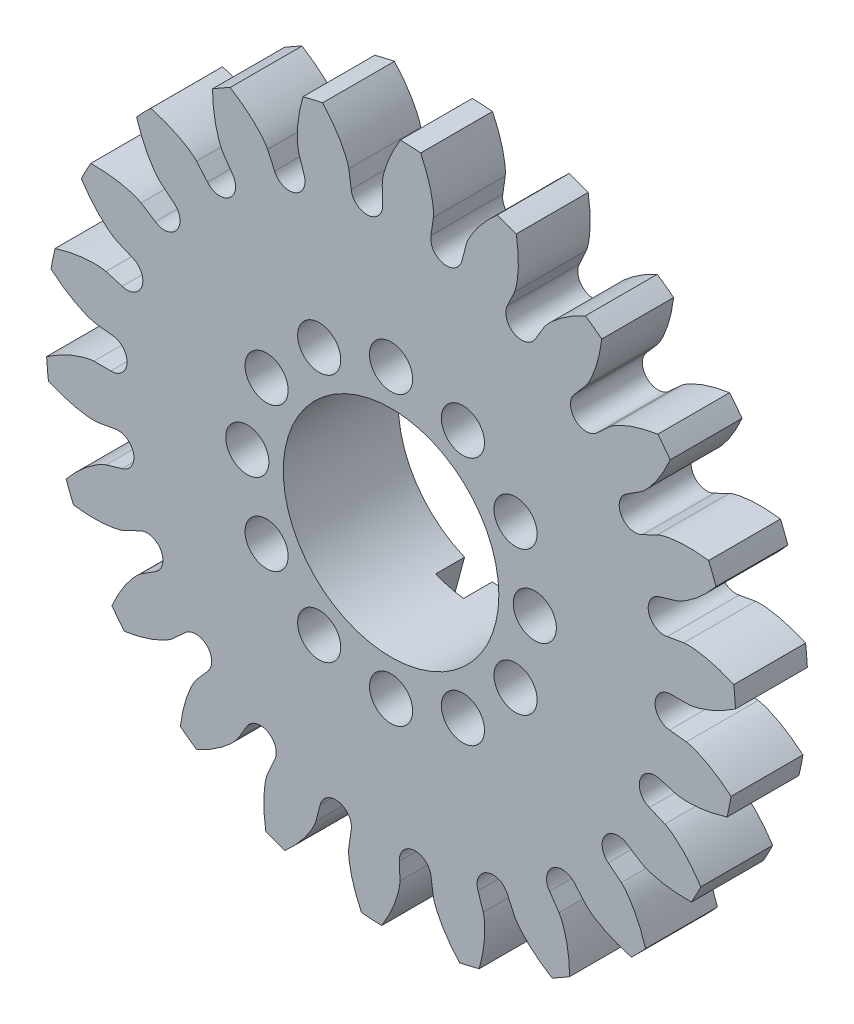
SolidWorks part; units mm, degrees
material "A2017"
ref_plane "正面" through (0, 0, 0) normal (0, 0, 1) x (1, 0, 0)
ref_plane "平面" through (0, 0, 0) normal (0, 1, 0) x (1, 0, 0)
ref_plane "右側面" through (0, 0, 0) normal (1, 0, 0) x (0, 0, -1)
sketch "ｽｹｯﾁ1" plane through (0, 0, 0) normal (1, 0, 0) x (0, 0, -1)
  line L0 (0, 0) -> (5.1985, 0) construction
  line L1 (0, 7.5) -> (5, 7.5)
  line L2 (5, 7.5) -> (5, 17.5)
  line L3 (5, 17.5) -> (0, 17.5)
  line L4 (0, 17.5) -> (0, 7.5)
  dimension "D1" = 35
  dimension "D3" = 5
  dimension "D5" = 15
revolve "回転1" add sketch "ｽｹｯﾁ1" angle 360 about L0
hole_wizard "M3 ねじ穴1" [suppressed] positions "ｽｹｯﾁ2" profile "ｽｹｯﾁ3" tap size "M3" standard "JIS"
sketch "ｽｹｯﾁ2" plane through (0, 0, -0.9) normal (0, 0, 1) x (1, 0, 0)
  point P0 (10, 0)
  point P3 (-5, 8.6603)
  point P6 (-5, -8.6603)
sketch "ｽｹｯﾁ3" plane through (10, 0, -0.9) normal (1, 0, 0) x (0, -1, 0)
  line L0 (0, 0) -> (0, 2)
  line L1 (0, 2) -> (1.25, 2)
  line L2 (1.25, 2) -> (1.25, 0)
  line L5 (1.25, 0) -> (0, 0)
  line L11 (0, -6.35) -> (0, 107.95) construction
  dimension "次ｻｰﾌｪｽまでのねじ下穴ﾄﾞﾘﾙ直径" = 2.5
  dimension "次ｻｰﾌｪｽまでのねじ下穴ﾄﾞﾘﾙの深さ" = 2
cosmetic thread "穴のねじ山1" [suppressed] parameters "D2"=3
cosmetic thread "穴のねじ山2" [suppressed] parameters "D2"=3
cosmetic thread "穴のねじ山3" [suppressed] parameters "D2"=3
sketch "ｽｹｯﾁ4" [suppressed] plane through (0, 0, -0.9) normal (0, 0, 1) x (1, 0, 0)
  line L0 (10, 0) -> (13.5, 0) construction
  line L1 (10, 3) -> (13.5, 3)
  line L2 (10, -3) -> (13.5, -3)
  line L3 (-5, -8.6603) -> (-6.75, -11.6913) construction
  line L4 (-2.4019, -10.1603) -> (-4.1519, -13.1913)
  line L5 (-7.5981, -7.1603) -> (-9.3481, -10.1913)
  line L6 (-5, 8.6603) -> (-6.75, 11.6913) construction
  line L7 (-7.5981, 7.1603) -> (-9.3481, 10.1913)
  line L8 (-2.4019, 10.1603) -> (-4.1519, 13.1913)
  line L9 (0, 0) -> (10, 0) construction
  circle A0 centre (0, 0) radius 13.5
  arc A1 (10, 3) -> (10, -3) centre (10, 0) ccw
  arc A2 (13.5, -3) -> (13.5, 3) centre (13.5, 0) ccw
  arc A3 (-2.4019, -10.1603) -> (-7.5981, -7.1603) centre (-5, -8.6603) ccw
  arc A4 (-9.3481, -10.1913) -> (-4.1519, -13.1913) centre (-6.75, -11.6913) ccw
  arc A5 (-7.5981, 7.1603) -> (-2.4019, 10.1603) centre (-5, 8.6603) ccw
  arc A6 (-4.1519, 13.1913) -> (-9.3481, 10.1913) centre (-6.75, 11.6913) ccw
  circle A7 centre (0, 0) radius 6
  arc A8 (5.44, 2.5311) -> (7.8667, 2.1092) centre (6.8, 3.1639) ccw
  arc A9 (5.44, -2.5311) -> (7.8667, -2.1092) centre (6.8, -3.1639) cw
  arc A10 (-4.912, -3.4456) -> (-5.76, -5.7581) centre (-6.14, -4.307) cw
  arc A11 (-0.528, -5.9767) -> (-2.1067, -7.8674) centre (-0.66, -7.4709) ccw
  arc A12 (-0.528, 5.9767) -> (-2.1067, 7.8674) centre (-0.66, 7.4709) cw
  arc A13 (-4.912, 3.4456) -> (-5.76, 5.7581) centre (-6.14, 4.307) ccw
  point P6 (11.75, 0)
  point P15 (-5.875, -10.1758)
  point P22 (-5.875, 10.1758)
  point P34 (0, 0)
  point P49 (0, 0)
  dimension "D1" = 27
  dimension "D4" = 12
  dimension "D5" = 3
  dimension "D2" = 6
  dimension "D3" = 3
  dimension "D6" = 3
extrude "ｶｯﾄ - 押し出し1" [suppressed] cut sketch "ｽｹｯﾁ4" against normal through all contours A7 A13 A5 L7 A0 L5 A3 A10 | A12 A7 A8 A1 L1 A0 L8 A5 | A7 A11 A3 L4 A0 L2 A1 A9
fillet "ﾌｨﾚｯﾄ1" [suppressed] radius 1.5
sketch "歯車作図" plane through (0, 0, 0) normal (0, 0, 1) x (1, 0, 0)
  line L0 (0, 0) -> (19.5, 0) construction
  line L1 (19.5, 0) -> (20.6732, 0)
  line L2 (0, 0) -> (23.9617, -1.3552)
  circle A0 centre (0, 0) radius 24
  circle A1 centre (0, 0) radius 22 construction
  circle A2 centre (0, 0) radius 20.6732 construction
  circle A3 centre (0, 0) radius 19.5 construction
  arc A4 (21.9649, -1.2422) -> (21.9976, 0.3279) centre (0, 0) ccw
  spline S0 degree 4 poles (20.6732, 0) (20.7051, 0.001) (20.7687, 0.005) (20.9463, 0.026) (21.2809, 0.0916) (21.7837, 0.2362) (22.4522, 0.5003) (23.2771, 0.9171) (24.1926, 1.4955) (25.1359, 2.2203) (26.08, 3.0881) (26.9525, 4.0273) (27.7551, 5.0268) (28.5256, 6.1294) (29.3868, 7.5551) (30.272, 9.3344) (31.1036, 11.4883) (31.787, 13.961) (32.2407, 16.4856) (32.4754, 19.0395) (32.5016, 21.6036) (32.3293, 24.162) (32.0137, 26.3829) (31.6314, 28.2668) (31.2413, 29.8196) (30.9314, 30.8974) (30.6411, 31.8121) (30.3814, 32.5713) (30.1659, 33.1706) (29.9364, 33.7758) (29.7054, 34.3599) (29.473, 34.9178) (29.2792, 35.3689) (29.0503, 35.8809) (28.8989, 36.2107) (28.6494, 36.7413) (28.448, 37.1504) (28.2002, 37.6458) (27.9718, 38.0834) (27.7218, 38.5532) (27.4776, 38.9955) (27.283, 39.341) (27.1562, 39.56) (27.0903, 39.6737) knots 0 0 0 0 0 0.002802 0.005604 0.015718 0.02996 0.048734 0.068727 0.096889 0.125051 0.153212 0.181374 0.209535 0.237696 0.271429 0.327752 0.384075 0.440398 0.496721 0.553044 0.609367 0.66569 0.722013 0.750174 0.778336 0.806497 0.820578 0.834659 0.84874 0.86282 0.876901 0.890982 0.900036 0.909091 0.920455 0.931818 0.943182 0.954545 0.965909 0.977273 0.988636 1 1 1 1 1 construction
  spline S1 degree 4 poles (20.6732, 0) (20.7051, 0.001) (20.7687, 0.005) (20.9463, 0.026) (21.2809, 0.0916) (21.7837, 0.2362) (22.4522, 0.5003) (23.2771, 0.9171) (24.1926, 1.4955) (25.1359, 2.2203) (26.08, 3.0881) (26.9525, 4.0273) (27.7551, 5.0268) (28.5256, 6.1294) (29.3868, 7.5551) (30.272, 9.3344) (31.1036, 11.4883) (31.787, 13.961) (32.2407, 16.4856) (32.4754, 19.0395) (32.5016, 21.6036) (32.3293, 24.162) (32.0137, 26.3829) (31.6314, 28.2668) (31.2413, 29.8196) (30.9314, 30.8974) (30.6411, 31.8121) (30.3814, 32.5713) (30.1659, 33.1706) (29.9364, 33.7758) (29.7054, 34.3599) (29.473, 34.9178) (29.2792, 35.3689) (29.11, 35.7473) (29.0321, 35.9192) (28.9931, 36.0043) knots 0 0 0 0 0 0.002802 0.005604 0.015718 0.02996 0.048734 0.068727 0.096889 0.125051 0.153212 0.181374 0.209535 0.237696 0.271429 0.327752 0.384075 0.440398 0.496721 0.553044 0.609367 0.66569 0.722013 0.750174 0.778336 0.806497 0.820578 0.834659 0.84874 0.86282 0.876901 0.890982 0.900036 0.909091 0.909091 0.909091 0.909091 0.909091
  dimension "歯先円直径" = 48
  dimension "基礎ピッチ円直径" = 44
  dimension "基礎円直径" = 41.3465
  dimension "全歯丈" = 4.5
  dimension "基準ピッチ" = 1.5708
sketch "ｽｹｯﾁ6" plane through (0, 0, 0) normal (0, 0, 1) x (1, 0, 0)
  circle A0 centre (0, 0) radius 24 construction
  circle A1 centre (0, 0) radius 24
  circle A3 centre (0, 0) radius 17.5
  circle A4 centre (0, 0) radius 17.5
  dimension "D1" = 0
extrude "ﾎﾞｽ - 押し出し1" add sketch "ｽｹｯﾁ6" against normal through all
sketch "ｽｹｯﾁ7" plane through (0, 0, 0) normal (0, 0, 1) x (1, 0, 0)
  line L0 (19.5, 0) -> (20.6732, 0) construction
  line L1 (0, 0) -> (23.9617, -1.3552) construction
  line L2 (19.5, 0) -> (20.6732, 0)
  line L3 (19.4689, -1.1011) -> (23.9617, -1.3552)
  circle A1 centre (0, 0) radius 24
  arc A2 (23.9617, -1.3552) -> (23.9612, 1.3645) centre (0, 0) ccw
  circle A3 centre (0, 0) radius 19.5 construction
  arc A4 (19.4689, -1.1011) -> (19.5, 0) centre (0, 0) ccw
  spline S0 degree 4 poles (12.6728, -1999.6488) (14.3151, 57.5876) (16.7687, 1.0731) (19.0837, -0.3395) (21.2809, 0.0916) (21.7837, 0.2362) (22.4522, 0.5003) (23.2771, 0.9171) (24.1926, 1.4955) (25.1359, 2.2203) (26.08, 3.0881) (26.9525, 4.0273) (27.7551, 5.0268) (28.5256, 6.1294) (29.3868, 7.5551) (30.272, 9.3344) (31.1036, 11.4883) (31.787, 13.961) (32.2407, 16.4856) (32.4754, 19.0395) (32.5016, 21.6036) (32.3293, 24.162) (32.0137, 26.3829) (31.6314, 28.2668) (31.2413, 29.8196) (30.9314, 30.8974) (30.6411, 31.8121) (30.3814, 32.5713) (30.1659, 33.1706) (29.9364, 33.7758) (29.7054, 34.3599) (29.473, 34.9178) (28.6142, 36.9169) (26.6056, 41.0517) (49.8954, -10.3734) (-803.7541, 1854.1196) knots -0.166761 -0.166761 -0.166761 -0.166761 -0.166761 0.002802 0.005604 0.015718 0.02996 0.048734 0.068727 0.096889 0.125051 0.153212 0.181374 0.209535 0.237696 0.271429 0.327752 0.384075 0.440398 0.496721 0.553044 0.609367 0.66569 0.722013 0.750174 0.778336 0.806497 0.820578 0.834659 0.84874 0.86282 0.876901 0.890982 0.900036 1.067877 1.067877 1.067877 1.067877 1.067877 only from (20.6732, 0) to (28.9931, 36.0043) construction
  spline S1 degree 4 poles (20.6732, 0) (20.7051, 0.001) (20.7687, 0.005) (20.9463, 0.026) (21.2809, 0.0916) (21.7837, 0.2362) (22.4522, 0.5003) (23.0956, 0.8254) (23.575, 1.1115) (23.8638, 1.2994) (23.9612, 1.3645) knots 0 0 0 0 0 0.002802 0.005604 0.015718 0.02996 0.048734 0.068727 0.079031 0.079031 0.079031 0.079031 0.079031
  dimension "D1" = 0
extrude "ｶｯﾄ - 押し出し2" cut sketch "ｽｹｯﾁ7" against normal through all
pattern_circular "円形ﾊﾟﾀｰﾝ1" count 22 over 360 about axis through (0, 0, 0) along (0, 0, 1) of "ｶｯﾄ - 押し出し2"
mirror "ﾐﾗｰ1" about plane through (19.4689, -1.1011, -5) normal (-0.0565, -0.9984, 0) of "円形ﾊﾟﾀｰﾝ1", "ｶｯﾄ - 押し出し2"
sketch "ｽｹｯﾁ8" plane through (0, 0, 0) normal (0, 0, 1) x (1, 0, 0)
  circle A0 centre (-7.0861, 18.1669) radius 1.1015
  arc A1 (-6.049, 18.5381) -> (-8.1006, 17.7378) centre (0, 0) ccw construction
extrude "ｶｯﾄ - 押し出し3" cut sketch "ｽｹｯﾁ8" against normal through all
pattern_circular "円形ﾊﾟﾀｰﾝ2" count 22 over 360 about axis through (0, 0, 0) along (0, 0, 1) of "ｶｯﾄ - 押し出し3"
sketch "ｽｹｯﾁ9" plane through (0, 0, 0) normal (0, 0, 1) x (1, 0, 0)
  line L0 (0, 0) -> (19, 0) construction
  line L1 (0, 0) -> (18.3526, -4.9176) construction
  line L2 (18.3526, 4.9176) -> (0, 0) construction
  circle A0 centre (0, 0) radius 16 construction
  circle A1 centre (0, 0) radius 22 construction
  arc A2 (18.3526, -4.9176) -> (18.3526, 4.9176) centre (0, 0) ccw construction
  arc A3 (21.2504, -5.694) -> (21.2504, 5.694) centre (0, 0) ccw
  arc A4 (15.4548, -4.1411) -> (15.4548, 4.1411) centre (0, 0) ccw
  arc A5 (15.4548, -4.1411) -> (21.2504, -5.694) centre (18.3526, -4.9176) ccw
  arc A6 (21.2504, 5.694) -> (15.4548, 4.1411) centre (18.3526, 4.9176) ccw
  arc A7 (4.9176, -18.3526) -> (13.435, -13.435) centre (0, 0) ccw construction
  arc A8 (5.694, -21.2504) -> (15.5563, -15.5563) centre (0, 0) ccw
  arc A9 (4.1411, -15.4548) -> (11.3137, -11.3137) centre (0, 0) ccw
  arc A10 (4.1411, -15.4548) -> (5.694, -21.2504) centre (4.9176, -18.3526) ccw
  arc A11 (15.5563, -15.5563) -> (11.3137, -11.3137) centre (13.435, -13.435) ccw
  arc A12 (-13.435, -13.435) -> (-4.9176, -18.3526) centre (0, 0) ccw construction
  arc A13 (-15.5563, -15.5563) -> (-5.694, -21.2504) centre (0, 0) ccw
  arc A14 (-11.3137, -11.3137) -> (-4.1411, -15.4548) centre (0, 0) ccw
  arc A15 (-11.3137, -11.3137) -> (-15.5563, -15.5563) centre (-13.435, -13.435) ccw
  arc A16 (-5.694, -21.2504) -> (-4.1411, -15.4548) centre (-4.9176, -18.3526) ccw
  arc A17 (-18.3526, 4.9176) -> (-18.3526, -4.9176) centre (0, 0) ccw construction
  arc A18 (-21.2504, 5.694) -> (-21.2504, -5.694) centre (0, 0) ccw
  arc A19 (-15.4548, 4.1411) -> (-15.4548, -4.1411) centre (0, 0) ccw
  arc A20 (-15.4548, 4.1411) -> (-21.2504, 5.694) centre (-18.3526, 4.9176) ccw
  arc A21 (-21.2504, -5.694) -> (-15.4548, -4.1411) centre (-18.3526, -4.9176) ccw
  arc A22 (-4.9176, 18.3526) -> (-13.435, 13.435) centre (0, 0) ccw construction
  arc A23 (-5.694, 21.2504) -> (-15.5563, 15.5563) centre (0, 0) ccw
  arc A24 (-4.1411, 15.4548) -> (-11.3137, 11.3137) centre (0, 0) ccw
  arc A25 (-4.1411, 15.4548) -> (-5.694, 21.2504) centre (-4.9176, 18.3526) ccw
  arc A26 (-15.5563, 15.5563) -> (-11.3137, 11.3137) centre (-13.435, 13.435) ccw
  arc A27 (13.435, 13.435) -> (4.9176, 18.3526) centre (0, 0) ccw construction
  arc A28 (15.5563, 15.5563) -> (5.694, 21.2504) centre (0, 0) ccw
  arc A29 (11.3137, 11.3137) -> (4.1411, 15.4548) centre (0, 0) ccw
  arc A30 (11.3137, 11.3137) -> (15.5563, 15.5563) centre (13.435, 13.435) ccw
  arc A31 (5.694, 21.2504) -> (4.1411, 15.4548) centre (4.9176, 18.3526) ccw
  point P6 (19, 0)
  point P20 (9.5, -16.4545)
  point P27 (-9.5, -16.4545)
  point P34 (-19, 0)
  point P41 (-9.5, 16.4545)
  point P48 (9.5, 16.4545)
  point P53 (0, 0)
  dimension "D1" = 32
  dimension "D2" = 44
  dimension "D3" = 6
  dimension "D4" = 30
  dimension "D5" = 6
extrude "ｶｯﾄ - 押し出し4" [suppressed] cut sketch "ｽｹｯﾁ9" against normal through all
sketch "ｽｹｯﾁ10" plane through (0, 0, -5) normal (0, 0, -1) x (-1, 0, 0)
  circle A0 centre (0, 0) radius 12.5
  circle A1 centre (0, 0) radius 7.5 construction
  circle A2 centre (0, 0) radius 7.5
  dimension "D1" = 25
extrude "ﾎﾞｽ - 押し出し2" add sketch "ｽｹｯﾁ10" along normal blind 3
sketch "ｽｹｯﾁ11" plane through (0, 0, 0) normal (0, 0, 1) x (1, 0, 0)
  line L0 (0, 10) -> (0, 0) construction
  circle A0 centre (0, 10) radius 1.5
  circle A1 centre (0, 0) radius 10 construction
  circle A2 centre (5, 8.6603) radius 1.5
  circle A3 centre (8.6603, 5) radius 1.5
  circle A4 centre (10, 0) radius 1.5
  circle A5 centre (8.6603, -5) radius 1.5
  circle A6 centre (5, -8.6603) radius 1.5
  circle A7 centre (0, -10) radius 1.5
  circle A8 centre (-5, -8.6603) radius 1.5
  circle A9 centre (-8.6603, -5) radius 1.5
  circle A10 centre (-10, 0) radius 1.5
  circle A11 centre (-8.6603, 5) radius 1.5
  circle A12 centre (-5, 8.6603) radius 1.5
  point P29 (0, 0)
  dimension "D1" = 3
  dimension "D2" = 20
  dimension "D3" = 12
extrude "ｶｯﾄ - 押し出し5" cut sketch "ｽｹｯﾁ11" against normal through all
sketch "ｽｹｯﾁ12" plane through (0, 0, -5) normal (0, 0, -1) x (-1, 0, 0)
  circle A0 centre (0, 0) radius 16.5
  circle A1 centre (0, 0) radius 12.5 construction
  circle A2 centre (0, 0) radius 12.5
  dimension "D1" = 4
extrude "ｶｯﾄ - 押し出し6" cut sketch "ｽｹｯﾁ12" against normal blind 3
sketch "ｽｹｯﾁ13" plane through (0, 0, -8) normal (0, 0, -1) x (-1, 0, 0)
  line L0 (-5, 8.6603) -> (0, 10) construction
  line L1 (-2.5, 9.3301) -> (0, 0) construction
  line L2 (3.2352, -12.0741) -> (-3.2352, 12.0741) construction
  line L3 (2.2693, -12.3329) -> (-4.2012, 11.8153)
  line L4 (4.2012, -11.8153) -> (-2.2693, 12.3329)
  arc A0 (2.2693, -12.3329) -> (4.2012, -11.8153) centre (3.2352, -12.0741) ccw
  arc A1 (-2.2693, 12.3329) -> (-4.2012, 11.8153) centre (-3.2352, 12.0741) ccw
  circle A2 centre (0, 0) radius 12.5 construction
  point P9 (0, 0)
  point P14 (-3.2352, 12.0741)
  dimension "D1" = 2
extrude "ｶｯﾄ - 押し出し7" cut sketch "ｽｹｯﾁ13" against normal blind 2
equation "\"モジュール\"= 2"
equation "\"歯数\"= 22"
equation "\"圧力角\"= 20"
equation "\"歯先円直径@歯車作図\" =  ( \"歯数\" + 2 )  * \"モジュール\""
equation "\"基礎ピッチ円直径@歯車作図\" = \"モジュール\" * \"歯数\""
equation "\"基礎円直径@歯車作図\" = \"歯数\" * \"モジュール\" * cos ( \"圧力角\" ) "
equation "\"全歯丈@歯車作図\" = 2.25 * \"モジュール\""
equation "\"基準ピッチ@歯車作図\" = PI * \"モジュール\" / 4"
equation "\"D1@円形ﾊﾟﾀｰﾝ1\"=\"歯数\""
equation "\"D1@円形ﾊﾟﾀｰﾝ2\"=\"歯数\""
